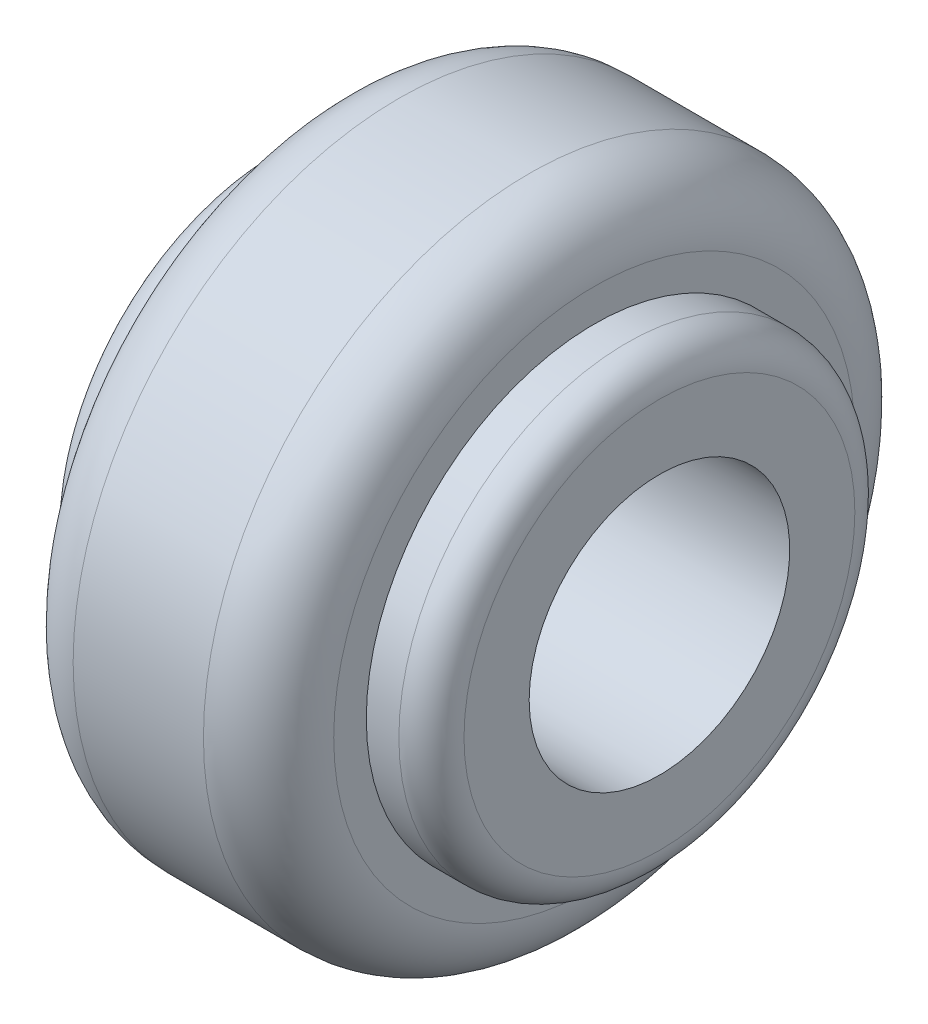
SolidWorks part; units mm, degrees
material "Nylon 6/10"
ref_plane "Front Plane" through (0, 0, 0) normal (0, 0, 1) x (1, 0, 0)
ref_plane "Top Plane" through (0, 0, 0) normal (0, 1, 0) x (1, 0, 0)
ref_plane "Right Plane" through (0, 0, 0) normal (1, 0, 0) x (0, 0, -1)
sketch "Sketch2" plane through (0, 0, 0) normal (0, 1, 0) x (1, 0, 0)
  line L0 (0, 6.35) -> (19.05, 6.35)
  line L1 (19.05, 6.35) -> (19.05, 11.1125)
  line L2 (19.05, 11.1125) -> (15.875, 11.1125)
  line L3 (15.875, 11.1125) -> (15.875, 15.875)
  line L4 (15.875, 15.875) -> (3.175, 15.875)
  line L5 (3.175, 15.875) -> (3.175, 11.1125)
  line L6 (3.175, 11.1125) -> (0, 11.1125)
  line L7 (0, 11.1125) -> (0, 6.35)
  line L8 (0, 0) -> (19.05, 0) construction
  dimension "D1" = 6.35
  dimension "D2" = 15.875
  dimension "D3" = 3.175
  dimension "D4" = 3.175
  dimension "D5" = 4.7625
  dimension "D6" = 19.05
revolve "Revolve1" add sketch "Sketch2" angle 360 about L8
fillet "Fillet2" radius 3.175 2 edges at (15.875, 0, 15.875) (3.175, 0, 15.875)
fillet "Fillet3" radius 1.5875 2 edges at (0, 0, 11.1125) (19.05, 0, 11.1125)
